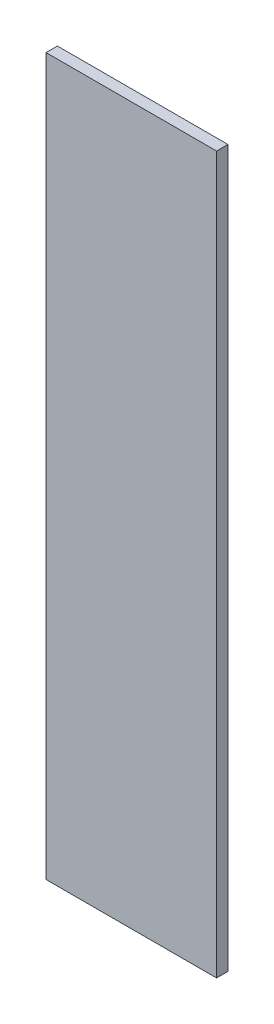
SolidWorks part; units mm, degrees
ref_plane "Front Plane" through (0, 0, 0) normal (0, 0, 1) x (1, 0, 0)
ref_plane "Top Plane" through (0, 0, 0) normal (0, 1, 0) x (1, 0, 0)
ref_plane "Right Plane" through (0, 0, 0) normal (1, 0, 0) x (0, 0, -1)
sketch "Sketch1" plane through (0, 0, 0) normal (0, 0, 1) x (1, 0, 0)
  line L1 (0, 0) -> (30, 0)
  line L2 (0, 0) -> (0, 126)
  line L3 (0, 126) -> (30, 126)
  line L4 (30, 0) -> (30, 126)
  dimension "D1" = 30
  dimension "D2" = 126
extrude "Profile" add sketch "Sketch1" along normal blind 2
equation "\"Profile_Depth\"= 2mm"
equation "\"D1@Profile\" = \"Profile_Depth\""
equation "\"Profile_Sketch_1\"= 30mm"
equation "\"D1@Sketch1\" = \"Profile_Sketch_1\""
equation "\"Profile_Sketch_2\"= 126mm"
equation "\"D2@Sketch1\" = \"Profile_Sketch_2\""
equation "\"EnvelopeWidth\"= 30mm"
equation "\"EnvelopeHeight\"= 126mm"
